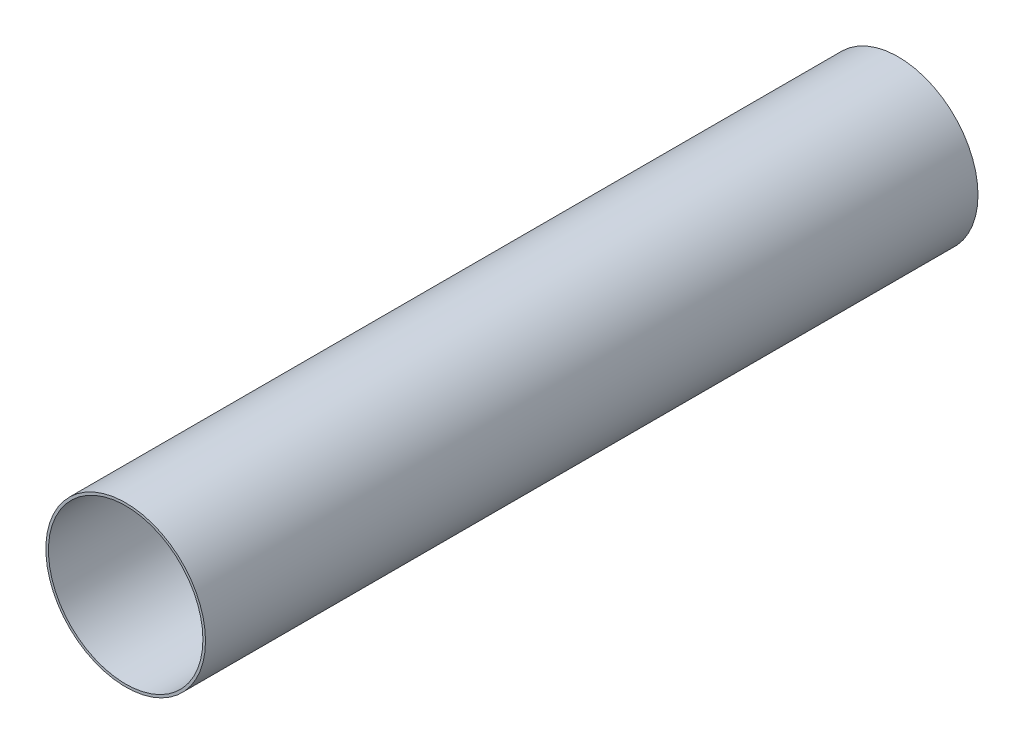
SolidWorks part; units mm, degrees
material "Acrílico (Impacto medio-alto)"
ref_plane "Alzado" through (0, 0, 0) normal (1, 0, 0) x (0, 1, 0)
ref_plane "Planta" through (0, 0, 0) normal (0, 0, 1) x (0, 1, 0)
ref_plane "Vista lateral" through (0, 0, 0) normal (0, 1, 0) x (-1, 0, 0)
sketch "Croquis1" plane through (0, 0, 0) normal (0, 0, 1) x (0, 1, 0)
  circle A0 centre (0, 0) radius 150
  circle A1 centre (0, 0) radius 155
  dimension "D1" = 300
  dimension "D2" = 5
extrude "Saliente-Extruir1" add sketch "Croquis1" along normal blind 1500
